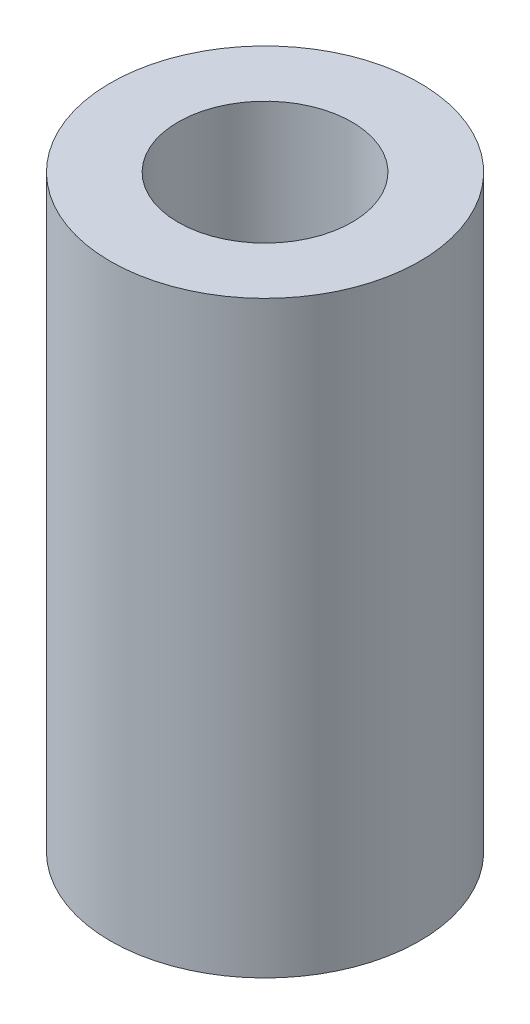
SolidWorks part; units mm, degrees
ref_plane "Front Plane" through (0, 0, 0) normal (0, 0, 1) x (1, 0, 0)
ref_plane "Top Plane" through (0, 0, 0) normal (0, 1, 0) x (1, 0, 0)
ref_plane "Right Plane" through (0, 0, 0) normal (1, 0, 0) x (0, 0, -1)
sketch "Sketch1" plane through (0, 0, 0) normal (0, 1, 0) x (1, 0, 0)
  circle A0 centre (0, 0) radius 1.632
  circle A1 centre (0, 0) radius 2.9019
  dimension "D1" = 3.2639
  dimension "D2" = 5.8039
extrude "Boss-Extrude1" add sketch "Sketch1" along normal blind 11.049
